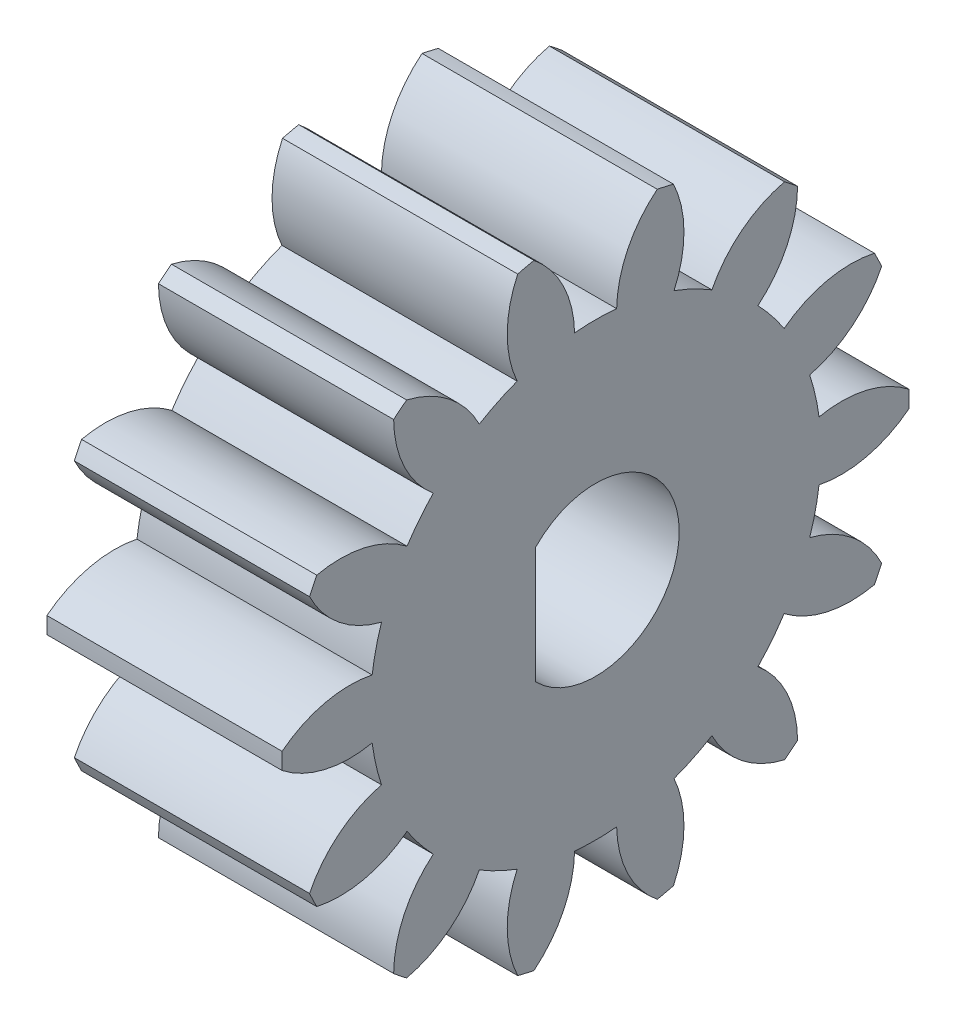
SolidWorks part; units mm, degrees
ref_plane "Plane1" through (0, 0, 0) normal (0, 0, 1) x (1, 0, 0)
ref_plane "Plane2" through (0, 0, 0) normal (0, 1, 0) x (1, 0, 0)
ref_plane "Plane3" through (0, 0, 0) normal (1, 0, 0) x (0, 0, -1)
sketch "HoldingSke" plane through (0, 0, 0) normal (0, 1, 0) x (1, 0, 0)
  line L0 (0, 0) -> (0.6469, -0.1613)
  line L1 (-15, 0) -> (100, 0) construction
  line L2 (0, 0) -> (-2.1039, 2.3779)
  line L3 (0, 0) -> (-11.863, 4.5341)
  line L4 (0, 0) -> (8.3795, 2.0892)
  line L5 (0, 0) -> (-46.8476, -17.4728)
  line L6 (0, 0) -> (-11.6055, -7.8303)
  line L7 (-2.1039, 2.3779) -> (8.6586, 51.2059)
  line L8 (-76.2, 54.61) -> (-75.2, 54.61)
  line L9 (-71.009, 38.7566) -> (-53.1078, 45.2721)
  line L10 (-76.2, 71.12) -> (104.1128, 71.12)
  line L11 (0, 0) -> (-14, 0)
  line L12 (-76.2, 101.6) -> (-76.147, 101.6)
  line L13 (24.9733, 27.94) -> (52.9518, 28.4284)
  line L14 (24.9733, 27.94) -> (24.9743, 27.94)
  line L15 (24.9733, 27.94) -> (100.4006, 29.5858)
  line L16 (-63.627, -1.5) -> (-12.827, -1.5)
  circle A0 centre (0, 0) radius 3
  circle A1 centre (0, 0) radius 8.624
  circle A2 centre (0, 0) radius 37.5
  circle A3 centre (0, 0) radius 3
  dimension "MHD" = 17.248
  dimension "Hub_dia" = 75
  dimension "Bore" = 6
  dimension "MBD" = 6
  dimension "Num_teeth" = 14
  dimension "Pitch" = 0.6667
  dimension "Overall_len" = 50
  dimension "Show_teeth" = 14
  dimension "Thickness" = 14
  dimension "OAL" = 50.0001
  dimension "T_dim" = 1
  dimension "Ap" = 20
  dimension "H" = 19.05
  dimension "Pitch_radius" = 180.3128
  dimension "Width" = 14
  dimension "Backlash" = 0.053
  dimension "Addendum_fac" = 1
  dimension "Dedendum_fac" = 1.25
  dimension "Clearance_fac" = 0.25
  dimension "Dedendum_add" = 0.001
  dimension "Module" = 1.5
sketch "BasProSke" plane through (0, 0, 0) normal (0, 1, 0) x (1, 0, 0)
  line L0 (-10, 0) -> (60, 0) construction
  line L1 (0, 0) -> (0, 12)
  line L2 (0, 0) -> (14, 0)
  line L3 (14, 0) -> (14, 12)
  line L4 (14, 12) -> (0, 12)
  dimension "Thickness" = 14
  dimension "Diameter" = 24
revolve "Base-Revolve" add sketch "BasProSke" angle 360 about L0
sketch "TooCutSke" plane through (0, 0, 0) normal (1, 0, 0) x (0, 0, -1)
  line L1 (0, 0) -> (0, 107) construction
  line L2 (0, 0) -> (-1.2683, 10.4231) construction
  line L3 (0, 0) -> (-4.648, 20.3643) construction
  line L4 (-1.2683, 10.4231) -> (-2.324, 10.1822) construction
  arc A0 (0.8048, 8.5864) -> (-0.8048, 8.5864) centre (0, 0) ccw
  arc A1 (2.3844, 11.7866) -> (-2.3844, 11.7866) centre (0, 0) ccw
  circle A2 centre (0, 0) radius 10.5 construction
  circle A3 centre (0, 0) radius 9.8668 construction
  arc A4 (-0.8048, 8.5864) -> (-2.3844, 11.7866) centre (-5.004, 8.5037) ccw
  arc A5 (2.3844, 11.7866) -> (0.8048, 8.5864) centre (5.004, 8.5037) ccw
  dimension "Root_dia" = 17.248
  dimension "Overcut_dia" = 24.0508
  dimension "Pitch_dia" = 21
  dimension "Base_dia" = 19.7335
  dimension "Flank_rad" = 4.2
  dimension "Half_ang" = 12.857
  dimension "Half_CT" = 1.0829
extrude "ToothCut" cut sketch "TooCutSke" along normal through all
fillet "Breaks" [suppressed] radius 0.03
fillet "RootFillets" [suppressed] radius 0.376
pattern_circular "TeethCuts" count 14 every 25.714 about axis through (-10, 0, 0) along (1, 0, 0) of "ToothCut", "RootFillets", "Breaks"
sketch "HubNeaOneSke" plane through (0, 0, 0) normal (-1, 0, 0) x (0, 0, 1)
  circle A0 centre (0, 0) radius 8.624
  dimension "Diameter" = 17.248
extrude "HubNearOne" [suppressed] add sketch "HubNeaOneSke" along normal blind 36.0001
sketch "HubNeaBotSke" plane through (0, 0, 0) normal (-1, 0, 0) x (0, 0, 1)
  circle A0 centre (0, 0) radius 8.624
  dimension "Diameter" = 17.248
extrude "HubNearBoth" [suppressed] add sketch "HubNeaBotSke" along normal blind 18
ref_plane "FarPln" through (14, 0, 0) normal (1, 0, 0) x (0, 0, -1)
sketch "HubFarSke" plane through (14, 0, 0) normal (1, 0, 0) x (0, 0, -1)
  circle A0 centre (0, 0) radius 8.624
  dimension "Diameter" = 17.248
extrude "HubFar" [suppressed] add sketch "HubFarSke" along normal blind 18
sketch "BorSke" plane through (0, 0, 0) normal (1, 0, 0) x (0, 0, -1)
  circle A0 centre (0, 0) radius 3
  dimension "Diameter" = 6
extrude "Bore" cut sketch "BorSke" along normal mid plane 100.0001
sketch "KeySke" plane through (0, 0, 0) normal (1, 0, 0) x (0, 0, -1)
  line L0 (-1, 0) -> (-1, 4)
  line L1 (-1, 4) -> (1, 4)
  line L2 (1, 4) -> (1, 0)
  line L3 (0, 0) -> (0, 34) construction
  line L4 (-1, 0) -> (1, 0)
  dimension "Offset" = 4
  dimension "Width" = 2
extrude "Keyway" [suppressed] cut sketch "KeySke" along normal mid plane 100.0001
pattern_circular "Keyway2" [suppressed] count 2 every 90 about axis through (-10, 0, 0) along (1, 0, 0)
sketch "Sketch1" plane through (14, 0, 0) normal (1, 0, 0) x (0, 0, -1)
  circle A0 centre (0, 0) radius 10.5 construction
  dimension "D1" = 21
sketch "Sketch2" plane through (14, 0, 0) normal (1, 0, 0) x (0, 0, -1)
  circle A0 centre (0, 0) radius 16.0863
extrude "Cut-Extrude1" cut sketch "Sketch2" against normal blind 5
sketch "Sketch3" plane through (9, 0, 0) normal (1, 0, 0) x (0, 0, -1)
  circle A0 centre (0, 0) radius 3.2
  dimension "D1" = 6.4
extrude "Cut-Extrude2" cut sketch "Sketch3" against normal through all
sketch "Sketch4" plane through (9, 0, 0) normal (1, 0, 0) x (0, 0, -1)
  line L0 (0, 0) -> (-3.2, 0) construction
  line L1 (-2.3, 2.2249) -> (-2.3, -2.2249)
  circle A0 centre (0, 0) radius 3.2 construction
  arc A1 (-2.3, 2.2249) -> (-2.3, -2.2249) centre (0, 0) ccw
  dimension "D1" = 0.9
extrude "Boss-Extrude1" add sketch "Sketch4" against normal up to surface (9 mm away) up to face at (0, 0, -3.2)
sketch "Sketch5" plane through (9, 0, 0) normal (1, 0, 0) x (0, 0, -1)
  circle A0 centre (0, 0) radius 10.5 construction
  dimension "D1" = 21
equation "' \"Module@HoldingSke\" = 6.35"
equation "' \"Num_teeth@HoldingSke\" = 12"
equation "' \"Ap@HoldingSke\" =  20"
equation "' \"Ap@HoldingSke\" = 20"
equation "' \"Width@HoldingSke\" = 0.5 * 25.4"
equation "' \"Hub_dia@HoldingSke\"= 1 * 25.4"
equation "' \"Hub_dia@HoldingSke\" = 1 * 25.4"
equation "' \"Overall_len@HoldingSke\" = 1.0 * 25.4"
equation "' \"Bore@HoldingSke\" = 0.75 * 25.4"
equation "' \"T_dim@HoldingSke\" = 0.1 * 25.4"
equation "' \"Width@KeySke\" = 0.25 * 25.4"
equation "' \"Show_teeth@HoldingSke\" = 13"
equation "' \"Backlash@HoldingSke\" = 0.009 * 25.4"
equation "' \"Addendum_fac@HoldingSke\" = 1.0"
equation "' \"Dedendum_fac@HoldingSke\" = 1.25"
equation "' \"Dedendum_add@HoldingSke\" = 0.00005 * 25.4"
equation "' \"Clearance_fac@HoldingSke\" = 0.25"
equation "\"Pitch@HoldingSke\" = 1 / \"Module@HoldingSke\""
equation "\"Overcut_dia@TooCutSke\" = (\"Num_teeth@HoldingSke\" + 2 * \"Addendum_fac@HoldingSke\") / \"Pitch@HoldingSke\" + 0.002 * 25.4"
equation "\"Pitch_dia@TooCutSke\" = \"Num_teeth@HoldingSke\" / \"Pitch@HoldingSke\""
equation "\"Base_dia@TooCutSke\" = \"Num_teeth@HoldingSke\" / \"Pitch@HoldingSke\" * cos((\"Ap@HoldingSke\"  * 3.14159265 / 180))"
equation "\"Root_dia@TooCutSke\" = (\"Num_teeth@HoldingSke\" + 2) / \"Pitch@HoldingSke\" - 2 * (\"Addendum_fac@HoldingSke\" + \"Dedendum_fac@HoldingSke\") / \"Pitch@HoldingSke\" - \"Dedendum_add@HoldingSke\" * 2"
equation "\"Half_ang@TooCutSke\" = 180 / \"Num_teeth@HoldingSke\""
equation "\"Half_CT@TooCutSke\" = \"Num_teeth@HoldingSke\" / \"Pitch@HoldingSke\" * sin((3.14159265 / 2 / \"Num_teeth@HoldingSke\")) / 2 - 7 * \"Backlash@HoldingSke\" / 4"
equation "\"Flank_rad@TooCutSke\" = \"Num_teeth@HoldingSke\" / \"Pitch@HoldingSke\" / 5"
equation "\"Radius@RootFillets\" = \"Clearance_fac@HoldingSke\" / \"Pitch@HoldingSke\" + \"Dedendum_add@HoldingSke\""
equation "\"Break_rad@Breaks\" = 0.02 / \"Pitch@HoldingSke\""
equation "\"Thickness@HoldingSke\" = \"Width@HoldingSke\""
equation "\"OAL@HoldingSke\" = \"Thickness@HoldingSke\""
equation "\"MHD@HoldingSke\" = (\"Num_teeth@HoldingSke\" + 2) / \"Pitch@HoldingSke\" - 2 * (\"Addendum_fac@HoldingSke\" + \"Dedendum_fac@HoldingSke\")  / \"Pitch@HoldingSke\" - \"Dedendum_add@HoldingSke\" * 2"
equation "\"MBD@HoldingSke\" = (\"Num_teeth@HoldingSke\" + 2) / \"Pitch@HoldingSke\" - 2 * (\"Addendum_fac@HoldingSke\" + \"Dedendum_fac@HoldingSke\")  / \"Pitch@HoldingSke\" - \"Dedendum_add@HoldingSke\" * 2 - 0.002 * 25.4"
equation "\"MHD@HoldingSke\" = ((sgn( \"MHD@HoldingSke\" - \"Hub_dia@HoldingSke\" )-1)*( \"MHD@HoldingSke\" - \"Hub_dia@HoldingSke\" ))/-2+ \"Hub_dia@HoldingSke\""
equation "\"MBD@HoldingSke\" = ((sgn( \"MBD@HoldingSke\" - \"Bore@HoldingSke\" )-1)*( \"MBD@HoldingSke\" - \"Bore@HoldingSke\" ))/-2+ \"Bore@HoldingSke\""
equation "\"OAL@HoldingSke\" = ((sgn( \"OAL@HoldingSke\" - \"Overall_len@HoldingSke\" )+1)*( \"OAL@HoldingSke\" - \"Overall_len@HoldingSke\" ))/2 + \"Overall_len@HoldingSke\" + 0.000002 * 25.4"
equation "\"Num_teeth@TeethCuts\" = int( \"Show_teeth@HoldingSke\" ) + 1"
equation "\"Num_teeth@TeethCuts\" = ((sgn( \"Num_teeth@TeethCuts\" - \"Num_teeth@HoldingSke\" )-1)*( \"Num_teeth@TeethCuts\" - \"Num_teeth@HoldingSke\" ))/-2+ \"Num_teeth@HoldingSke\""
equation "\"Num_teeth@TeethCuts\" = ((sgn( \"Num_teeth@TeethCuts\" - 2.0)+1)*( \"Num_teeth@TeethCuts\" - 2.0))/2 +2.0"
equation "\"Angle@TeethCuts\" = 360.0 / \"Num_teeth@HoldingSke\""
equation "\"Diameter@BasProSke\" = (\"Num_teeth@HoldingSke\" + 2 * \"Addendum_fac@HoldingSke\") / \"Pitch@HoldingSke\""
equation "\"Thickness@BasProSke\"  = \"Thickness@HoldingSke\""
equation "' \"Fillet_rad@BasProSke\" =  \"Thickness@HoldingSke\" * 0.05"
equation "' \"Fillet_rad@BasProSke\" = \"Thickness@HoldingSke\" * 0.05"
equation "\"MHD@HoldingSke\" = ((sgn( \"MHD@HoldingSke\" - \"Root_dia@TooCutSke\" )-1)*( \"MHD@HoldingSke\" - \"Root_dia@TooCutSke\" ))/-2+ \"Root_dia@TooCutSke\""
equation "\"Diameter@HubNeaOneSke\" = \"MHD@HoldingSke\""
equation "\"Length@HubNearOne\" = \"OAL@HoldingSke\" - \"Thickness@BasProSke\""
equation "\"Diameter@HubNeaBotSke\" = \"MHD@HoldingSke\""
equation "\"Length@HubNearBoth\" = ( \"OAL@HoldingSke\" - \"Thickness@BasProSke\" ) / 2.0"
equation "\"Thickness@FarPln\" = \"Thickness@BasProSke\""
equation "\"Diameter@HubFarSke\" = \"MHD@HoldingSke\""
equation "\"Length@HubFar\" = ( \"OAL@HoldingSke\" - \"Thickness@BasProSke\" ) / 2.0"
equation "\"Diameter@BorSke\" = \"MBD@HoldingSke\""
equation "\"D1@Bore\" = \"OAL@HoldingSke\" * 2.0"
equation "\"D1@Keyway\" = \"OAL@HoldingSke\" * 2.0"
equation "\"Offset@KeySke\" = \"T_dim@HoldingSke\" + \"MBD@HoldingSke\" / 2.0"
